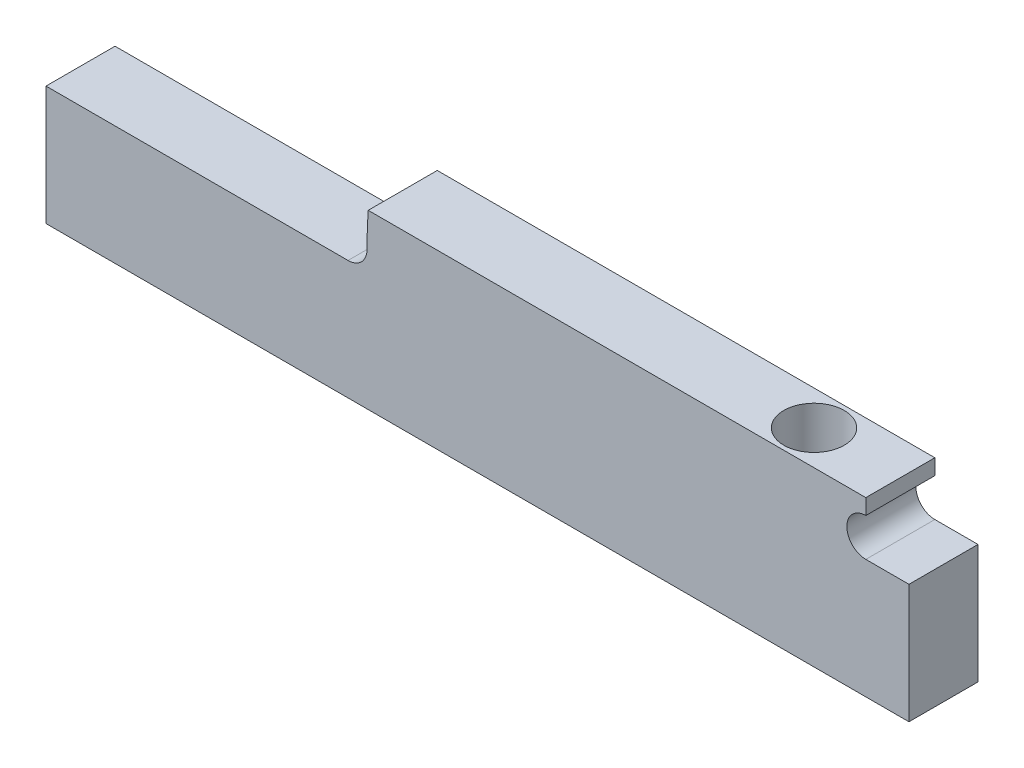
SolidWorks part; units mm, degrees
ref_plane "Front Plane" through (0, 0, 0) normal (0, 0, 1) x (1, 0, 0)
ref_plane "Top Plane" through (0, 0, 0) normal (0, 1, 0) x (1, 0, 0)
ref_plane "Right Plane" through (0, 0, 0) normal (1, 0, 0) x (0, 0, -1)
sketch "Sketch1" plane through (0, 0, 0) normal (0, 0, 1) x (1, 0, 0)
  line L0 (-56.5737, 24.5873) -> (1.0877, 24.5873)
  line L1 (6.0877, 18.3873) -> (6.0877, 4.5873)
  line L2 (6.0877, 4.5873) -> (-93.9123, 4.5873)
  line L3 (-93.9123, 4.5873) -> (-93.9123, 18.3873)
  line L4 (1.0877, 22.7873) -> (1.0877, 24.5873)
  line L5 (-58.9123, 18.3873) -> (-93.9123, 18.3873)
  line L6 (1.0877, 18.3873) -> (6.0877, 18.3873)
  arc A0 (1.0877, 22.7873) -> (1.0877, 18.3873) centre (1.0877, 20.5873) ccw
  arc A1 (-58.9123, 18.3873) -> (-56.7123, 20.5873) centre (-58.9123, 20.5873) ccw
  arc A2 (-56.5737, 24.5873) -> (-56.7123, 20.5873) centre (1.0877, 20.5873) ccw
extrude "Boss-Extrude2" add sketch "Sketch1" along normal blind 8
sketch "Sketch2" plane through (0, 24.5873, 0) normal (0, 1, 0) x (1, 0, 0)
  circle A0 centre (-8.9123, -4) radius 2
extrude "Cut-Extrude1" cut sketch "Sketch2" against normal blind 20
sketch "Sketch3" plane through (0, 24.5873, 0) normal (0, 1, 0) x (1, 0, 0)
  circle A0 centre (-8.9123, -4) radius 3.5
extrude "Cut-Extrude2" cut sketch "Sketch3" against normal blind 15
